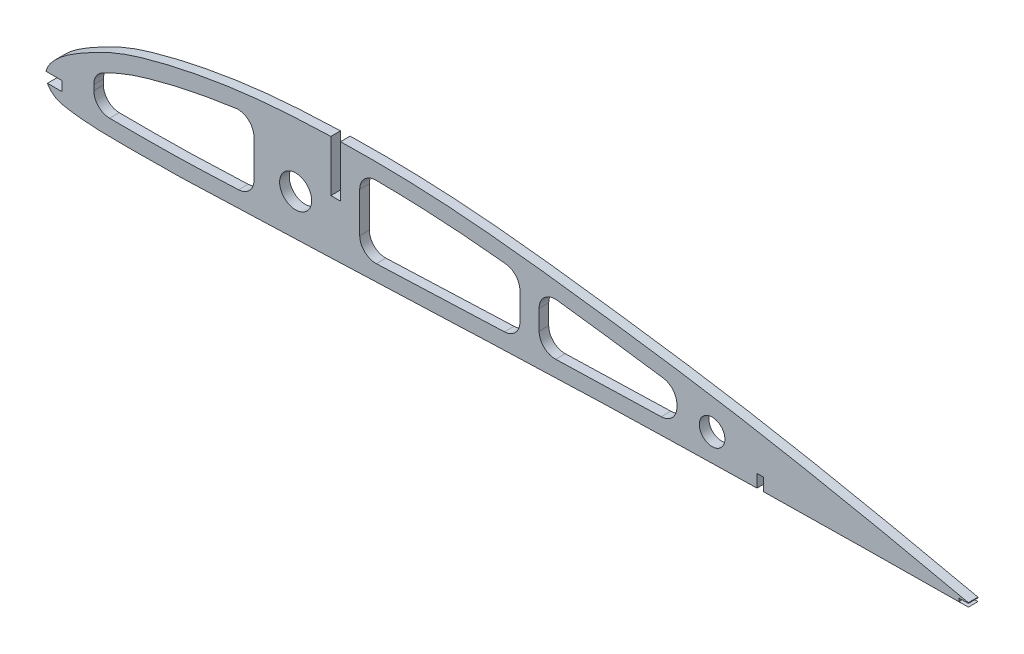
SolidWorks part; units mm, degrees
material "轻木"
ref_plane "前视基准面" through (0, 0, 0) normal (0, 0, 1) x (1, 0, 0)
ref_plane "上视基准面" through (0, 0, 0) normal (0, 1, 0) x (1, 0, 0)
ref_plane "右视基准面" through (0, 0, 0) normal (1, 0, 0) x (0, 0, -1)
other "Configuration Table"
curve "曲线1"
  spline degree 3 poles (300, 0.375, 0) (299.2857, 0.5355, 0) (297.8572, 0.8566, 0) (295.7147, 1.3378, 0) (293.5725, 1.8185, 0) (291.4302, 2.2982, 0) (289.2875, 2.7769, 0) (287.1442, 3.2543, 0) (285.001, 3.7299, 0) (282.8583, 4.2033, 0) (280.7163, 4.6744, 0) (278.5743, 5.1433, 0) (276.432, 5.6099, 0) (274.2889, 6.0741, 0) (272.145, 6.5358, 0) (269.2891, 7.1472, 0) (265.721, 7.9038, 0) (261.4399, 8.8, 0) (257.1573, 9.6847, 0) (252.8725, 10.5577, 0) (248.585, 11.4191, 0) (244.2942, 12.2686, 0) (240.0067, 13.1048, 0) (235.7231, 13.9276, 0) (231.4437, 14.735, 0) (227.1623, 15.5265, 0) (222.8779, 16.3002, 0) (218.5899, 17.0545, 0) (214.2976, 17.7876, 0) (210.0082, 18.4964, 0) (205.7223, 19.1793, 0) (201.441, 19.8388, 0) (197.1575, 20.4787, 0) (192.8717, 21.1016, 0) (188.5834, 21.71, 0) (184.2928, 22.3067, 0) (180.0042, 22.8936, 0) (175.7188, 23.4732, 0) (171.4371, 24.0431, 0) (167.1545, 24.6013, 0) (162.8704, 25.1452, 0) (158.5838, 25.6724, 0) (154.2938, 26.1804, 0) (150.0066, 26.6658, 0) (145.7226, 27.1265, 0) (141.4425, 27.5584, 0) (137.1601, 27.958, 0) (132.875, 28.3213, 0) (128.5869, 28.6439, 0) (124.2953, 28.9218, 0) (120.0053, 29.1506, 0) (115.7177, 29.3264, 0) (111.4337, 29.4514, 0) (107.1488, 29.5275, 0) (102.863, 29.5565, 0) (98.5762, 29.5401, 0) (94.2882, 29.4801, 0) (89.9957, 29.378, 0) (85.6999, 29.236, 0) (81.4026, 29.047, 0) (77.1093, 28.8043, 0) (72.8211, 28.5008, 0) (68.5389, 28.1296, 0) (64.264, 27.6835, 0) (60.7007, 27.2426, 0) (57.8461, 26.8442, 0) (55.696, 26.5216, 0) (53.5496, 26.1773, 0) (51.4067, 25.8115, 0) (49.2673, 25.4247, 0) (47.1314, 25.0171, 0) (44.9882, 24.5868, 0) (42.838, 24.1341, 0) (40.6818, 23.6568, 0) (38.5315, 23.1552, 0) (36.3875, 22.6273, 0) (34.2503, 22.0712, 0) (32.1202, 21.4847, 0) (30.3423, 20.9664, 0) (28.9132, 20.5311, 0) (27.8303, 20.1897, 0) (26.7518, 19.8362, 0) (25.6784, 19.4687, 0) (24.6112, 19.0858, 0) (23.551, 18.6856, 0) (22.4821, 18.2598, 0) (21.4059, 17.8057, 0) (20.3222, 17.3242, 0) (19.2465, 16.8243, 0) (18.1774, 16.3076, 0) (17.1139, 15.7762, 0) (16.0546, 15.2317, 0) (14.9819, 14.6674, 0) (13.8954, 14.0851, 0) (12.7977, 13.4827, 0) (11.7087, 12.8677, 0) (10.6313, 12.2387, 0) (9.5687, 11.5942, 0) (8.5237, 10.9329, 0) (7.6518, 10.3543, 0) (6.9458, 9.8665, 0) (6.3985, 9.4746, 0) (5.8573, 9.0705, 0) (5.3218, 8.651, 0) (4.7913, 8.2128, 0) (4.2653, 7.7527, 0) (3.6165, 7.1497, 0) (2.8604, 6.3846, 0) (2.0362, 5.4343, 0) (1.2959, 4.4252, 0) (0.6772, 3.3675, 0) (0.2189, 2.2697, 0) (-0.0383, 1.1392, 0) (-0.0456, 0.0749, 0) (0.1619, -0.885, 0) (0.4986, -1.7375, 0) (0.9635, -2.5517, 0) (1.5376, -3.3119, 0) (2.2026, -4.0019, 0) (2.94, -4.6051, 0) (3.6355, -5.044, 0) (4.2555, -5.3464, 0) (4.779, -5.5548, 0) (5.3118, -5.728, 0) (5.8521, -5.8723, 0) (6.398, -5.9938, 0) (6.9478, -6.0987, 0) (7.671, -6.2224, 0) (8.5669, -6.3647, 0) (9.636, -6.5177, 0) (10.7063, -6.6545, 0) (11.7778, -6.7754, 0) (12.8506, -6.8809, 0) (13.9246, -6.9713, 0) (14.9978, -7.047, 0) (16.0697, -7.1082, 0) (17.1403, -7.1566, 0) (18.2115, -7.1941, 0) (19.2831, -7.2222, 0) (20.3552, -7.2427, 0) (21.4275, -7.2573, 0) (22.4998, -7.2676, 0) (23.5718, -7.2752, 0) (24.6434, -7.2803, 0) (25.7147, -7.2832, 0) (26.7859, -7.2843, 0) (27.8572, -7.2839, 0) (28.9285, -7.2822, 0) (30.3573, -7.2788, 0) (32.1433, -7.2727, 0) (34.2864, -7.2613, 0) (36.4292, -7.2444, 0) (38.5718, -7.2208, 0) (40.7144, -7.1891, 0) (42.8572, -7.148, 0) (45.0005, -7.0962, 0) (47.1439, -7.0325, 0) (49.2871, -6.9587, 0) (51.4297, -6.8772, 0) (53.572, -6.7902, 0) (55.7143, -6.6999, 0) (57.857, -6.6086, 0) (60.7142, -6.4884, 0) (64.2858, -6.3465, 0) (68.5714, -6.1868, 0) (72.8565, -6.0353, 0) (77.1416, -5.8893, 0) (81.427, -5.7463, 0) (85.7132, -5.6038, 0) (90.0001, -5.4593, 0) (94.287, -5.3101, 0) (98.5731, -5.1566, 0) (102.8583, -4.9992, 0) (107.1431, -4.8383, 0) (111.4281, -4.6742, 0) (115.7138, -4.5074, 0) (120.0001, -4.3383, 0) (124.2865, -4.1673, 0) (128.5722, -3.9953, 0) (132.8572, -3.8233, 0) (137.142, -3.6525, 0) (141.4271, -3.4838, 0) (145.7131, -3.3181, 0) (149.9996, -3.1567, 0) (154.286, -3.0004, 0) (158.5714, -2.8495, 0) (162.8564, -2.7043, 0) (167.1412, -2.5651, 0) (171.4266, -2.4321, 0) (175.7128, -2.3056, 0) (179.9996, -2.1858, 0) (184.2862, -2.0731, 0) (188.5719, -1.9664, 0) (192.857, -1.8646, 0) (197.1419, -1.7668, 0) (201.4272, -1.6719, 0) (205.7132, -1.5788, 0) (209.9999, -1.4865, 0) (214.2864, -1.3941, 0) (218.5722, -1.3027, 0) (222.8572, -1.2136, 0) (227.142, -1.128, 0) (231.4272, -1.0471, 0) (235.7132, -0.9723, 0) (239.9998, -0.9046, 0) (244.2864, -0.8454, 0) (248.5722, -0.7928, 0) (252.8573, -0.7451, 0) (257.1422, -0.7003, 0) (261.4274, -0.6568, 0) (265.7134, -0.6127, 0) (269.2855, -0.574, 0) (272.1433, -0.5408, 0) (274.2862, -0.5157, 0) (276.4287, -0.4908, 0) (278.5712, -0.4671, 0) (280.7137, -0.4452, 0) (282.8567, -0.4258, 0) (285, -0.4096, 0) (287.1432, -0.3973, 0) (289.2862, -0.3884, 0) (291.4287, -0.3824, 0) (293.5711, -0.3786, 0) (295.7137, -0.3765, 0) (297.8567, -0.3754, 0) (299.2855, -0.3751, 0) (300, -0.375, 0) knots 0 0 0 0 0.003574 0.007146 0.010718 0.01429 0.017862 0.021434 0.025008 0.028577 0.032145 0.035713 0.03928 0.042847 0.046415 0.049985 0.057103 0.064219 0.071333 0.078448 0.085563 0.092679 0.099797 0.106885 0.11397 0.121053 0.128137 0.13522 0.142305 0.149391 0.15644 0.163488 0.170534 0.17758 0.184627 0.191675 0.198725 0.205755 0.212782 0.219809 0.226834 0.233861 0.240889 0.24792 0.254921 0.26192 0.268917 0.275914 0.28291 0.289907 0.296905 0.303879 0.310852 0.317824 0.324796 0.331771 0.338748 0.345728 0.352728 0.359727 0.366723 0.373717 0.380709 0.387701 0.394695 0.398233 0.40177 0.405307 0.408843 0.41238 0.415918 0.419457 0.42305 0.426643 0.430235 0.433828 0.43742 0.441014 0.444611 0.446459 0.448306 0.450153 0.451999 0.453844 0.455687 0.45753 0.459459 0.461388 0.463318 0.465249 0.467183 0.469121 0.471062 0.4731 0.475138 0.477173 0.479204 0.481227 0.483239 0.48524 0.486334 0.487428 0.488525 0.48963 0.490748 0.491883 0.493041 0.495071 0.497131 0.499176 0.501171 0.503098 0.50496 0.506796 0.508242 0.509728 0.511253 0.512804 0.514366 0.515919 0.517444 0.518368 0.519283 0.520192 0.521101 0.522011 0.522922 0.523833 0.525592 0.527349 0.529104 0.530859 0.532612 0.534366 0.53612 0.537863 0.539607 0.54135 0.543094 0.544839 0.546584 0.548329 0.550073 0.551817 0.55356 0.555302 0.557045 0.558788 0.560532 0.564019 0.567506 0.570992 0.574478 0.577965 0.581452 0.584939 0.588429 0.591918 0.595406 0.598895 0.602383 0.605872 0.609363 0.616342 0.623319 0.630295 0.637271 0.644247 0.651224 0.658203 0.665183 0.672161 0.679137 0.686114 0.69309 0.700068 0.707048 0.714028 0.721006 0.727983 0.73496 0.741937 0.748915 0.755896 0.762874 0.769851 0.776826 0.783801 0.790777 0.797753 0.804732 0.811709 0.818683 0.825657 0.83263 0.839604 0.846578 0.853555 0.860532 0.867506 0.874479 0.881452 0.888424 0.895399 0.902375 0.90935 0.916324 0.923296 0.930267 0.937239 0.944213 0.951188 0.954676 0.958163 0.961649 0.965135 0.96862 0.972107 0.975595 0.979082 0.982569 0.986054 0.98954 0.993026 0.996512 1 1 1 1
curve "曲线2"
  spline degree 3 poles (299.6892, 0.0825, 0) (300.1498, -0.0478, 0) (299.7114, 0.1074, 0) (299.5104, 0.1872, 0) (299.2477, 0.2871, 0) (298.8504, 0.4413, 0) (298.294, 0.6613, 0) (297.5919, 0.9463, 0) (296.8903, 1.2362, 0) (296.0644, 1.581, 0) (295.1136, 1.9799, 0) (294.0373, 2.431, 0) (292.9597, 2.8788, 0) (291.7683, 3.3665, 0) (290.4608, 3.8877, 0) (289.0365, 4.4399, 0) (287.6073, 4.9796, 0) (286.0635, 5.5484, 0) (284.4048, 6.1444, 0) (282.6311, 6.7664, 0) (280.8534, 7.377, 0) (278.9651, 8.0149, 0) (276.9667, 8.6805, 0) (274.8582, 9.373, 0) (272.7471, 10.0574, 0) (270.5382, 10.7652, 0) (268.2318, 11.4959, 0) (265.8278, 12.2485, 0) (263.4214, 12.9932, 0) (260.9293, 13.7558, 0) (258.3517, 14.5354, 0) (255.6885, 15.3308, 0) (253.0225, 16.1168, 0) (250.2835, 16.9138, 0) (247.4714, 17.7205, 0) (244.5864, 18.536, 0) (241.6982, 19.3402, 0) (238.749, 20.1489, 0) (235.7391, 20.9612, 0) (232.6684, 21.7757, 0) (229.594, 22.5763, 0) (226.4711, 23.374, 0) (223.2997, 24.1675, 0) (220.08, 24.9553, 0) (216.8561, 25.726, 0) (213.5945, 26.4871, 0) (210.2953, 27.2373, 0) (206.9588, 27.975, 0) (203.6178, 28.6919, 0) (200.2497, 29.3918, 0) (196.8549, 30.0732, 0) (193.4336, 30.7349, 0) (190.0077, 31.3718, 0) (186.5618, 31.9862, 0) (183.0963, 32.577, 0) (179.6117, 33.1436, 0) (176.1229, 33.6833, 0) (172.6234, 34.197, 0) (169.1136, 34.6844, 0) (165.5943, 35.1447, 0) (162.0713, 35.5767, 0) (158.5465, 35.9798, 0) (155.0205, 36.3535, 0) (151.4939, 36.6979, 0) (147.9646, 37.0129, 0) (144.4431, 37.2978, 0) (140.9302, 37.5529, 0) (137.4264, 37.7777, 0) (133.9208, 37.9727, 0) (130.4332, 38.1365, 0) (126.9642, 38.269, 0) (123.5147, 38.3706, 0) (120.0643, 38.4412, 0) (116.6408, 38.4803, 0) (113.2449, 38.4881, 0) (109.8772, 38.4649, 0) (106.5099, 38.4098, 0) (103.1795, 38.3231, 0) (99.8867, 38.2053, 0) (96.6323, 38.0567, 0) (93.3796, 37.8749, 0) (90.1728, 37.6618, 0) (87.0127, 37.4182, 0) (83.9, 37.1447, 0) (80.7905, 36.8368, 0) (77.7347, 36.4989, 0) (74.7332, 36.1323, 0) (71.7867, 35.7377, 0) (68.8452, 35.3075, 0) (65.9638, 34.8492, 0) (63.1431, 34.3642, 0) (60.3838, 33.8535, 0) (57.6314, 33.3063, 0) (54.9457, 32.7337, 0) (52.327, 32.1376, 0) (49.7758, 31.5197, 0) (47.2337, 30.8655, 0) (44.763, 30.1905, 0) (42.364, 29.4973, 0) (40.0371, 28.7872, 0) (37.7217, 28.0406, 0) (35.4836, 27.2778, 0) (33.323, 26.5013, 0) (31.2399, 25.7132, 0) (29.1709, 24.8888, 0) (27.1829, 24.0541, 0) (25.2756, 23.212, 0) (23.4491, 22.3647, 0) (21.6401, 21.481, 0) (19.9159, 20.5922, 0) (18.2759, 19.7016, 0) (16.7198, 18.8121, 0) (15.1846, 17.8866, 0) (13.7354, 16.9627, 0) (12.3708, 16.045, 0) (11.0909, 15.1361, 0) (9.8373, 14.192, 0) (8.6721, 13.2572, 0) (7.5935, 12.336, 0) (6.5993, 11.4319, 0) (5.6356, 10.4933, 0) (4.7571, 9.5716, 0) (3.961, 8.6731, 0) (3.2484, 7.802, 0) (2.5791, 6.9017, 0) (2.0018, 6.0303, 0) (1.5119, 5.1928, 0) (1.098, 4.3932, 0) (0.723, 3.565, 0) (0.4148, 2.7772, 0) (0.1635, 2.0409, 0) (-0.0076, 1.362, 0) (-0.0857, 0.6761, 0) (-0.0312, 0.0318, 0) (0.1575, -0.5446, 0) (0.4284, -1.0495, 0) (0.7766, -1.5095, 0) (1.2499, -1.9767, 0) (1.8739, -2.4002, 0) (2.6419, -2.7457, 0) (3.4475, -3.0028, 0) (4.3968, -3.243, 0) (5.4726, -3.4987, 0) (6.6732, -3.7581, 0) (7.8724, -3.9885, 0) (9.2039, -4.2095, 0) (10.6736, -4.4054, 0) (12.2821, -4.571, 0) (13.8972, -4.6995, 0) (15.6445, -4.8094, 0) (17.5211, -4.9053, 0) (19.5261, -4.9826, 0) (21.5305, -5.0368, 0) (23.661, -5.0721, 0) (25.9181, -5.0854, 0) (28.3014, -5.0749, 0) (30.6852, -5.0437, 0) (33.1885, -4.993, 0) (35.8107, -4.9237, 0) (38.5514, -4.8343, 0) (41.2914, -4.7299, 0) (44.1429, -4.6075, 0) (47.1057, -4.467, 0) (50.1792, -4.3077, 0) (53.2522, -4.1367, 0) (56.4269, -3.9498, 0) (59.7026, -3.7473, 0) (63.0791, -3.5293, 0) (66.4551, -3.3033, 0) (69.9209, -3.0645, 0) (73.4761, -2.8134, 0) (77.1202, -2.5502, 0) (80.764, -2.2824, 0) (84.4846, -2.0051, 0) (88.2815, -1.7191, 0) (92.1543, -1.4245, 0) (96.027, -1.128, 0) (99.9621, -0.8252, 0) (103.9592, -0.5167, 0) (108.0179, -0.2032, 0) (112.0767, 0.1098, 0) (116.1823, 0.4251, 0) (120.3344, 0.742, 0) (124.5324, 1.0596, 0) (128.7308, 1.3739, 0) (132.9595, 1.6861, 0) (137.2181, 1.9957, 0) (141.506, 2.3018, 0) (145.7945, 2.6016, 0) (150.096, 2.8954, 0) (154.41, 3.1825, 0) (158.7362, 3.4618, 0) (163.063, 3.7316, 0) (167.3848, 3.9907, 0) (171.7011, 4.2382, 0) (176.0115, 4.4733, 0) (180.3226, 4.6957, 0) (184.6083, 4.9033, 0) (188.8679, 5.0957, 0) (193.1011, 5.2721, 0) (197.335, 5.4325, 0) (201.5222, 5.5742, 0) (205.6623, 5.6969, 0) (209.7546, 5.8004, 0) (213.8473, 5.8854, 0) (217.8716, 5.9498, 0) (221.8268, 5.9942, 0) (225.7124, 6.0188, 0) (229.598, 6.0233, 0) (233.3935, 6.0071, 0) (237.0983, 5.971, 0) (240.7119, 5.9157, 0) (244.325, 5.8393, 0) (247.8275, 5.7436, 0) (251.2186, 5.6301, 0) (254.498, 5.5, 0) (257.7765, 5.3484, 0) (260.9253, 5.1809, 0) (263.9441, 4.9996, 0) (266.8324, 4.8058, 0) (269.7191, 4.5899, 0) (272.4587, 4.362, 0) (275.0509, 4.1249, 0) (277.4951, 3.8799, 0) (279.9368, 3.6105, 0) (282.2113, 3.3338, 0) (284.3185, 3.0537, 0) (286.2585, 2.7745, 0) (288.195, 2.4723, 0) (289.9467, 2.1761, 0) (291.5141, 1.8919, 0) (292.8979, 1.6262, 0) (294.2788, 1.3456, 0) (295.4709, 1.0894, 0) (296.4751, 0.8638, 0) (297.2928, 0.6738, 0) (298.1076, 0.4784, 0) (298.7442, 0.3204, 0) (299.1896, 0.208, 0) (299.4728, 0.1348, 0) (299.6892, 0.0825, 0) (300.1498, -0.0478, 0) (299.7114, 0.1074, 0) knots -0.001345 -0.000897 -0.000449 0 0.000432 0.000863 0.001295 0.001726 0.002951 0.004176 0.0054 0.006625 0.008509 0.010392 0.012274 0.014158 0.016623 0.019088 0.021553 0.024019 0.027053 0.030085 0.033118 0.036152 0.039734 0.043315 0.046896 0.050478 0.054544 0.058608 0.062672 0.066738 0.071224 0.075709 0.080193 0.084679 0.089518 0.094356 0.099193 0.104032 0.10916 0.114286 0.119411 0.124539 0.129889 0.135237 0.140585 0.145936 0.151451 0.156964 0.162478 0.167993 0.173617 0.17924 0.184862 0.190486 0.196184 0.20188 0.207576 0.213274 0.219003 0.22473 0.230457 0.236185 0.241905 0.247622 0.253339 0.259058 0.264725 0.270389 0.276054 0.281721 0.287291 0.29286 0.298428 0.303998 0.309434 0.314867 0.320301 0.325737 0.330995 0.336251 0.341507 0.346766 0.351809 0.356851 0.361892 0.366936 0.371734 0.37653 0.381327 0.386125 0.390654 0.395182 0.399709 0.404238 0.408475 0.41271 0.416945 0.421182 0.425109 0.429034 0.432959 0.436885 0.44048 0.444073 0.447666 0.451261 0.454511 0.457759 0.461007 0.464256 0.467149 0.470041 0.472933 0.475826 0.47836 0.480893 0.483425 0.485956 0.488123 0.490291 0.49246 0.494634 0.496453 0.49827 0.500081 0.501882 0.503328 0.504776 0.506239 0.507727 0.50887 0.510003 0.51111 0.512198 0.513104 0.514027 0.514959 0.515886 0.517235 0.518584 0.51995 0.521324 0.523324 0.525303 0.52727 0.529235 0.531836 0.534446 0.537062 0.539679 0.542921 0.546158 0.549393 0.552628 0.556473 0.560319 0.564166 0.568014 0.57244 0.576864 0.581288 0.585714 0.590681 0.595647 0.600613 0.605581 0.611042 0.616501 0.62196 0.627422 0.633319 0.639214 0.645109 0.651006 0.657275 0.663542 0.669809 0.676078 0.682648 0.689216 0.695784 0.702355 0.70915 0.715943 0.722736 0.729531 0.73647 0.743406 0.750342 0.757281 0.764278 0.771273 0.778268 0.785265 0.792232 0.799197 0.806162 0.81313 0.819969 0.826805 0.833641 0.840479 0.847087 0.853692 0.860297 0.866904 0.873175 0.879445 0.885714 0.891986 0.897819 0.90365 0.909481 0.915314 0.920611 0.925907 0.931202 0.936499 0.941172 0.945842 0.950513 0.955185 0.95915 0.963114 0.967077 0.971042 0.974206 0.977368 0.98053 0.983693 0.985968 0.988241 0.990515 0.992789 0.994144 0.995498 0.996852 0.998206 0.998655 0.999103 0.999551 1 1.000432 1.000863 1.001295 periodic
sketch "草图1" plane through (0, 0, 0) normal (0, 0, 1) x (1, 0, 0)
  line L1 (290, 2.6177) -> (290, -0.3866)
  line L2 (289, 1.8162) -> (289, 0.6101)
  line L3 (0, 0) -> (0, 30) construction
  line L4 (-6, -1.5) -> (6, -1.5)
  line L5 (-6, -1.5) -> (-6, 1.5)
  line L6 (-6, 1.5) -> (6, 1.5)
  line L7 (6, -1.5) -> (6, 1.5)
  line L8 (-6, -1.5) -> (6, 1.5) construction
  line L9 (-6, 1.5) -> (6, -1.5) construction
  line L10 (-1000, 0) -> (49000, 0) construction
  line L11 (90, 29.3715) -> (93, 29.3715)
  line L12 (90, 29.3715) -> (90, 12.3715)
  line L13 (90, 12.3715) -> (93, 12.3715)
  line L14 (93, 29.3715) -> (93, 12.3715)
  line L16 (223, -1.2113) -> (225, -1.2113)
  line L17 (223, -1.2113) -> (223, 3.7887)
  line L18 (223, 3.7887) -> (225, 3.7887)
  line L19 (225, -1.2113) -> (225, 3.7887)
  line L20 (289, 0.6101) -> (286, 0.6101)
  line L21 (289, 0.6101) -> (289, 1.6101)
  line L22 (289, 1.6101) -> (286, 1.6101)
  line L23 (286, 0.6101) -> (286, 1.6101)
  circle A0 centre (79, 8) radius 5
  circle A1 centre (209, 8) radius 4
  spline S0 degree 3 poles (2664.3845, 5390.8144) (1028.5028, -174.9169) (663.7122, -81.3233) (295.7147, 1.3378) (293.5725, 1.8185) (291.4302, 2.2982) (289.2875, 2.7769) (287.1442, 3.2543) (285.001, 3.7299) (282.8583, 4.2033) (280.7163, 4.6744) (278.5743, 5.1433) (276.432, 5.6099) (274.2889, 6.0741) (272.145, 6.5358) (269.2891, 7.1472) (265.721, 7.9038) (261.4399, 8.8) (257.1573, 9.6847) (252.8725, 10.5577) (248.585, 11.4191) (244.2942, 12.2686) (240.0067, 13.1048) (234.2978, 14.2013) (228.5907, 15.2685) (222.8779, 16.3002) (218.5899, 17.0545) (214.2976, 17.7876) (210.0082, 18.4964) (205.7223, 19.1793) (201.441, 19.8388) (197.1575, 20.4787) (192.8717, 21.1016) (188.5834, 21.71) (184.2928, 22.3067) (180.0042, 22.8936) (175.7188, 23.4732) (171.4371, 24.0431) (167.1545, 24.6013) (162.8704, 25.1452) (158.5838, 25.6724) (154.2938, 26.1804) (150.0066, 26.6658) (145.7226, 27.1265) (141.4425, 27.5584) (137.1601, 27.958) (132.875, 28.3213) (128.5869, 28.6439) (124.2953, 28.9218) (120.0053, 29.1506) (115.7177, 29.3264) (111.4337, 29.4514) (107.1488, 29.5275) (102.863, 29.5565) (98.5762, 29.5401) (94.2882, 29.4801) (89.9957, 29.378) (85.6999, 29.236) (81.4026, 29.047) (77.1093, 28.8043) (72.8211, 28.5008) (68.5389, 28.1296) (64.264, 27.6835) (60.7007, 27.2426) (57.1284, 26.744) (53.5478, 26.188) (49.9791, 25.5605) (47.1314, 25.0171) (44.9882, 24.5868) (42.838, 24.1341) (40.6818, 23.6568) (38.5315, 23.1552) (36.3875, 22.6273) (34.2503, 22.0712) (32.1202, 21.4847) (30.3423, 20.9664) (28.9132, 20.5311) (27.8303, 20.1897) (26.7518, 19.8362) (25.6784, 19.4687) (24.6112, 19.0858) (23.551, 18.6856) (22.4821, 18.2598) (21.4059, 17.8057) (20.3222, 17.3242) (19.2465, 16.8243) (18.1774, 16.3076) (17.1139, 15.7762) (16.0546, 15.2317) (14.9819, 14.6674) (13.8954, 14.0851) (12.7977, 13.4827) (11.7087, 12.8677) (10.6313, 12.2387) (9.5687, 11.5942) (8.5237, 10.9329) (7.6518, 10.3543) (6.9458, 9.8665) (6.3985, 9.4746) (5.8573, 9.0705) (5.3218, 8.651) (4.7913, 8.2128) (4.2653, 7.7527) (3.6165, 7.1497) (2.8604, 6.3846) (2.0362, 5.4343) (1.2959, 4.4252) (0.6772, 3.3675) (0.2189, 2.2697) (-0.0383, 1.1392) (-0.0456, 0.0749) (0.1619, -0.885) (0.4986, -1.7375) (0.9635, -2.5517) (1.5376, -3.3119) (2.2026, -4.0019) (2.94, -4.6051) (3.6355, -5.044) (4.2555, -5.3464) (4.779, -5.5548) (5.3118, -5.728) (5.8521, -5.8723) (6.398, -5.9938) (6.9478, -6.0987) (7.671, -6.2224) (8.5669, -6.3647) (9.9918, -6.5686) (11.4199, -6.7402) (12.8506, -6.8809) (13.9246, -6.9713) (14.9978, -7.047) (16.0697, -7.1082) (17.1403, -7.1566) (18.2115, -7.1941) (19.2831, -7.2222) (20.3552, -7.2427) (21.4275, -7.2573) (22.4998, -7.2676) (23.5718, -7.2752) (24.6434, -7.2803) (25.7147, -7.2832) (27.143, -7.2847) (28.5715, -7.283) (30.3573, -7.2788) (32.1433, -7.2727) (34.2864, -7.2613) (36.4292, -7.2444) (38.5718, -7.2208) (40.7144, -7.1891) (42.8572, -7.148) (45.0005, -7.0962) (47.1439, -7.0325) (49.2871, -6.9587) (51.4297, -6.8772) (54.2862, -6.7612) (57.1429, -6.6386) (60.7142, -6.4884) (64.2858, -6.3465) (69.9995, -6.1336) (75.7132, -5.9369) (81.427, -5.7463) (85.7132, -5.6038) (90.0001, -5.4593) (94.287, -5.3101) (98.5731, -5.1566) (102.8583, -4.9992) (108.5717, -4.7846) (114.2856, -4.5638) (120.0001, -4.3383) (124.2865, -4.1673) (128.5722, -3.9953) (132.8572, -3.8233) (137.142, -3.6525) (141.4271, -3.4838) (145.7131, -3.3181) (149.9996, -3.1567) (154.286, -3.0004) (158.5714, -2.8495) (164.2846, -2.656) (171.4272, -2.4288) (179.9991, -2.1823) (187.1429, -2.0003) (192.857, -1.8646) (197.1419, -1.7668) (201.4272, -1.6719) (205.7132, -1.5788) (209.9999, -1.4865) (214.2864, -1.3941) (218.5722, -1.3027) (222.8572, -1.2136) (227.142, -1.128) (231.4272, -1.0471) (235.7132, -0.9723) (239.9998, -0.9046) (244.2864, -0.8454) (248.5722, -0.7928) (252.8573, -0.7451) (258.5708, -0.6854) (264.285, -0.6282) (269.2855, -0.574) (272.1433, -0.5408) (274.2862, -0.5157) (276.4287, -0.4908) (278.5712, -0.4671) (280.7137, -0.4452) (282.8567, -0.4258) (285, -0.4096) (287.1432, -0.3973) (289.2862, -0.3884) (291.4287, -0.3824) (293.5711, -0.3786) (295.7137, -0.3765) (581.7502, -0.2419) (867.0763, -15.0378) (1150.1739, 5872.6366) knots -1.830244 -1.830244 -1.830244 -1.830244 0.003574 0.007146 0.010718 0.01429 0.017862 0.021434 0.025008 0.028577 0.032145 0.035713 0.03928 0.042847 0.046415 0.049985 0.057103 0.064219 0.071333 0.078448 0.085563 0.092679 0.099797 0.106885 0.121053 0.128137 0.13522 0.142305 0.149391 0.15644 0.163488 0.170534 0.17758 0.184627 0.191675 0.198725 0.205755 0.212782 0.219809 0.226834 0.233861 0.240889 0.24792 0.254921 0.26192 0.268917 0.275914 0.28291 0.289907 0.296905 0.303879 0.310852 0.317824 0.324796 0.331771 0.338748 0.345728 0.352728 0.359727 0.366723 0.373717 0.380709 0.387701 0.394695 0.398233 0.405307 0.41238 0.415918 0.419457 0.42305 0.426643 0.430235 0.433828 0.43742 0.441014 0.444611 0.446459 0.448306 0.450153 0.451999 0.453844 0.455687 0.45753 0.459459 0.461388 0.463318 0.465249 0.467183 0.469121 0.471062 0.4731 0.475138 0.477173 0.479204 0.481227 0.483239 0.48524 0.486334 0.487428 0.488525 0.48963 0.490748 0.491883 0.493041 0.495071 0.497131 0.499176 0.501171 0.503098 0.50496 0.506796 0.508242 0.509728 0.511253 0.512804 0.514366 0.515919 0.517444 0.518368 0.519283 0.520192 0.521101 0.522011 0.522922 0.523833 0.525592 0.527349 0.530859 0.532612 0.534366 0.53612 0.537863 0.539607 0.54135 0.543094 0.544839 0.546584 0.548329 0.550073 0.551817 0.55356 0.555302 0.558788 0.560532 0.564019 0.567506 0.570992 0.574478 0.577965 0.581452 0.584939 0.588429 0.591918 0.595406 0.598895 0.605872 0.609363 0.616342 0.623319 0.637271 0.644247 0.651224 0.658203 0.665183 0.672161 0.679137 0.686114 0.700068 0.707048 0.714028 0.721006 0.727983 0.73496 0.741937 0.748915 0.755896 0.762874 0.769851 0.776826 0.790777 0.804732 0.818683 0.825657 0.83263 0.839604 0.846578 0.853555 0.860532 0.867506 0.874479 0.881452 0.888424 0.895399 0.902375 0.90935 0.916324 0.923296 0.930267 0.944213 0.951188 0.954676 0.958163 0.961649 0.965135 0.96862 0.972107 0.975595 0.979082 0.982569 0.986054 0.98954 0.993026 0.996512 2.385691 2.385691 2.385691 2.385691 only from (300, 0.375) to (300, -0.375) construction
  spline S1 degree 3 poles (290, 2.6177) (289.0482, 2.8302) (287.3817, 3.2016) (285.001, 3.7299) (282.8583, 4.2033) (280.7163, 4.6744) (278.5743, 5.1433) (276.432, 5.6099) (274.2889, 6.0741) (272.145, 6.5358) (269.2891, 7.1472) (265.721, 7.9038) (261.4399, 8.8) (257.1573, 9.6847) (252.8725, 10.5577) (248.585, 11.4191) (244.2942, 12.2686) (240.0067, 13.1048) (234.2978, 14.2013) (228.5907, 15.2685) (222.8779, 16.3002) (218.5899, 17.0545) (214.2976, 17.7876) (210.0082, 18.4964) (205.7223, 19.1793) (201.441, 19.8388) (197.1575, 20.4787) (192.8717, 21.1016) (188.5834, 21.71) (184.2928, 22.3067) (180.0042, 22.8936) (175.7188, 23.4732) (171.4371, 24.0431) (167.1545, 24.6013) (162.8704, 25.1452) (158.5838, 25.6724) (154.2938, 26.1804) (150.0066, 26.6658) (145.7226, 27.1265) (141.4425, 27.5584) (137.1601, 27.958) (132.875, 28.3213) (128.5869, 28.6439) (124.2953, 28.9218) (120.0053, 29.1506) (115.7177, 29.3264) (111.4337, 29.4514) (107.1488, 29.5275) (102.863, 29.5565) (98.5762, 29.5401) (94.2882, 29.4801) (89.9957, 29.378) (85.6999, 29.236) (81.4026, 29.047) (77.1093, 28.8043) (72.8211, 28.5008) (68.5389, 28.1296) (64.264, 27.6835) (60.7007, 27.2426) (57.1284, 26.744) (53.5478, 26.188) (49.9791, 25.5605) (47.1314, 25.0171) (44.9882, 24.5868) (42.838, 24.1341) (40.6818, 23.6568) (38.5315, 23.1552) (36.3875, 22.6273) (34.2503, 22.0712) (32.1202, 21.4847) (30.3423, 20.9664) (28.9132, 20.5311) (27.8303, 20.1897) (26.7518, 19.8362) (25.6784, 19.4687) (24.6112, 19.0858) (23.551, 18.6856) (22.4821, 18.2598) (21.4059, 17.8057) (20.3222, 17.3242) (19.2465, 16.8243) (18.1774, 16.3076) (17.1139, 15.7762) (16.0546, 15.2317) (14.9819, 14.6674) (13.8954, 14.0851) (12.7977, 13.4827) (11.7087, 12.8677) (10.6313, 12.2387) (9.5687, 11.5942) (8.5237, 10.9329) (7.6518, 10.3543) (6.9458, 9.8665) (6.3985, 9.4746) (5.8573, 9.0705) (5.3218, 8.651) (4.7913, 8.2128) (4.2653, 7.7527) (3.6165, 7.1497) (2.8604, 6.3846) (2.0362, 5.4343) (1.2959, 4.4252) (0.6772, 3.3675) (0.2189, 2.2697) (-0.0383, 1.1392) (-0.0456, 0.0749) (0.1619, -0.885) (0.4986, -1.7375) (0.9635, -2.5517) (1.5376, -3.3119) (2.2026, -4.0019) (2.94, -4.6051) (3.6355, -5.044) (4.2555, -5.3464) (4.779, -5.5548) (5.3118, -5.728) (5.8521, -5.8723) (6.398, -5.9938) (6.9478, -6.0987) (7.671, -6.2224) (8.5669, -6.3647) (9.9918, -6.5686) (11.4199, -6.7402) (12.8506, -6.8809) (13.9246, -6.9713) (14.9978, -7.047) (16.0697, -7.1082) (17.1403, -7.1566) (18.2115, -7.1941) (19.2831, -7.2222) (20.3552, -7.2427) (21.4275, -7.2573) (22.4998, -7.2676) (23.5718, -7.2752) (24.6434, -7.2803) (25.7147, -7.2832) (27.143, -7.2847) (28.5715, -7.283) (30.3573, -7.2788) (32.1433, -7.2727) (34.2864, -7.2613) (36.4292, -7.2444) (38.5718, -7.2208) (40.7144, -7.1891) (42.8572, -7.148) (45.0005, -7.0962) (47.1439, -7.0325) (49.2871, -6.9587) (51.4297, -6.8772) (54.2862, -6.7612) (57.1429, -6.6386) (60.7142, -6.4884) (64.2858, -6.3465) (69.9995, -6.1336) (75.7132, -5.9369) (81.427, -5.7463) (85.7132, -5.6038) (90.0001, -5.4593) (94.287, -5.3101) (98.5731, -5.1566) (102.8583, -4.9992) (108.5717, -4.7846) (114.2856, -4.5638) (120.0001, -4.3383) (124.2865, -4.1673) (128.5722, -3.9953) (132.8572, -3.8233) (137.142, -3.6525) (141.4271, -3.4838) (145.7131, -3.3181) (149.9996, -3.1567) (154.286, -3.0004) (158.5714, -2.8495) (164.2846, -2.656) (171.4272, -2.4288) (179.9991, -2.1823) (187.1429, -2.0003) (192.857, -1.8646) (197.1419, -1.7668) (201.4272, -1.6719) (205.7132, -1.5788) (209.9999, -1.4865) (214.2864, -1.3941) (218.5722, -1.3027) (222.8572, -1.2136) (227.142, -1.128) (231.4272, -1.0471) (235.7132, -0.9723) (239.9998, -0.9046) (244.2864, -0.8454) (248.5722, -0.7928) (252.8573, -0.7451) (258.5708, -0.6854) (264.285, -0.6282) (269.2855, -0.574) (272.1433, -0.5408) (274.2862, -0.5157) (276.4287, -0.4908) (278.5712, -0.4671) (280.7137, -0.4452) (282.8567, -0.4258) (285, -0.4096) (287.1432, -0.3973) (288.8099, -0.3904) (289.7621, -0.3873) (290, -0.3866) knots 0.016674 0.016674 0.016674 0.016674 0.021434 0.025008 0.028577 0.032145 0.035713 0.03928 0.042847 0.046415 0.049985 0.057103 0.064219 0.071333 0.078448 0.085563 0.092679 0.099797 0.106885 0.121053 0.128137 0.13522 0.142305 0.149391 0.15644 0.163488 0.170534 0.17758 0.184627 0.191675 0.198725 0.205755 0.212782 0.219809 0.226834 0.233861 0.240889 0.24792 0.254921 0.26192 0.268917 0.275914 0.28291 0.289907 0.296905 0.303879 0.310852 0.317824 0.324796 0.331771 0.338748 0.345728 0.352728 0.359727 0.366723 0.373717 0.380709 0.387701 0.394695 0.398233 0.405307 0.41238 0.415918 0.419457 0.42305 0.426643 0.430235 0.433828 0.43742 0.441014 0.444611 0.446459 0.448306 0.450153 0.451999 0.453844 0.455687 0.45753 0.459459 0.461388 0.463318 0.465249 0.467183 0.469121 0.471062 0.4731 0.475138 0.477173 0.479204 0.481227 0.483239 0.48524 0.486334 0.487428 0.488525 0.48963 0.490748 0.491883 0.493041 0.495071 0.497131 0.499176 0.501171 0.503098 0.50496 0.506796 0.508242 0.509728 0.511253 0.512804 0.514366 0.515919 0.517444 0.518368 0.519283 0.520192 0.521101 0.522011 0.522922 0.523833 0.525592 0.527349 0.530859 0.532612 0.534366 0.53612 0.537863 0.539607 0.54135 0.543094 0.544839 0.546584 0.548329 0.550073 0.551817 0.55356 0.555302 0.558788 0.560532 0.564019 0.567506 0.570992 0.574478 0.577965 0.581452 0.584939 0.588429 0.591918 0.595406 0.598895 0.605872 0.609363 0.616342 0.623319 0.637271 0.644247 0.651224 0.658203 0.665183 0.672161 0.679137 0.686114 0.700068 0.707048 0.714028 0.721006 0.727983 0.73496 0.741937 0.748915 0.755896 0.762874 0.769851 0.776826 0.790777 0.804732 0.818683 0.825657 0.83263 0.839604 0.846578 0.853555 0.860532 0.867506 0.874479 0.881452 0.888424 0.895399 0.902375 0.90935 0.916324 0.923296 0.930267 0.944213 0.951188 0.954676 0.958163 0.961649 0.965135 0.96862 0.972107 0.975595 0.979082 0.982569 0.98373 0.98373 0.98373 0.98373
  spline S2 degree 1 poles (289, 1.8162) (289, 0.6101) knots 0 0 1 1 construction
  spline S3 degree 3 poles (289, 1.8162) (276.9573, 4.5023) (258.8616, 8.3976) (234.6482, 13.1528) (216.4485, 16.4789) (198.1829, 19.3716) (179.8506, 21.9241) (161.5032, 24.3586) (143.1279, 26.4732) (124.7122, 28.0438) (106.2546, 28.676) (87.7718, 28.43) (72.4033, 27.5865) (60.1859, 26.2263) (51.081, 24.7981) (42.0339, 23.0001) (34.582, 21.1749) (28.6974, 19.4456) (24.362, 17.9834) (20.1748, 16.2079) (16.0789, 14.1399) (12.0403, 11.9468) (8.1401, 9.5604) (5.1537, 7.3164) (3.1001, 5.2006) (1.8138, 3.4707) (0.9689, 1.5796) (0.9059, -0.2656) (1.7459, -2.0716) (3.1431, -3.6011) (4.8543, -4.6194) (6.9276, -5.1056) (9.209, -5.4548) (12.22, -5.8429) (16.0201, -6.1427) (20.6095, -6.2611) (25.2315, -6.2869) (31.3974, -6.2803) (39.1073, -6.2407) (48.3368, -6.0221) (57.5799, -5.613) (66.8407, -5.2429) (76.0966, -4.9217) (88.436, -4.516) (103.8531, -3.9731) (122.3546, -3.2481) (140.8578, -2.4955) (159.3685, -1.8041) (177.8842, -1.2225) (196.4034, -0.7749) (214.9166, -0.3802) (233.434, 0.0126) (251.9612, 0.2567) (270.4719, 0.4292) (282.8248, 0.5874) (289, 0.6101) knots 0.017978 0.017978 0.017978 0.017978 0.078237 0.108366 0.138495 0.168624 0.198753 0.228882 0.259011 0.28914 0.319269 0.349398 0.379527 0.394592 0.409656 0.424721 0.439785 0.447318 0.45485 0.462382 0.469915 0.477447 0.484979 0.492511 0.496277 0.500044 0.50381 0.507576 0.511342 0.515108 0.518874 0.52264 0.526407 0.530173 0.537705 0.545237 0.552769 0.560302 0.575366 0.590431 0.605495 0.62056 0.635624 0.650689 0.680818 0.710947 0.741076 0.771205 0.801334 0.831463 0.861593 0.891722 0.921851 0.95198 0.982109 0.982109 0.982109 0.982109
  point P8 (0, 0)
  dimension "D9" = 10
  dimension "D10" = 8
  dimension "D1" = 290
  dimension "D2" = 1
  dimension "D3" = 12
  dimension "D4" = 3
  dimension "D5" = 30
  dimension "D6" = 3
  dimension "D7" = 17
  dimension "D8" = 90
  dimension "D11" = 130
  dimension "D12" = 11
  dimension "D13" = 8
  dimension "D14" = 5
  dimension "D15" = 2
  dimension "D16" = 130
  dimension "D17" = 1
  dimension "D18" = 3
extrude "凸台-拉伸1" add sketch "草图1" along normal blind 3 contours L2 S3 | S1 L1
sketch "草图3" plane through (0, 0, 0) normal (0, 0, 1) x (1, 0, 0)
  line L12 (16, 5.403) -> (16, 3.7496)
  line L13 (66, 16.1752) -> (66, 4.5297)
  line L14 (99, 18.546) -> (99, 6.0517)
  line L15 (149, 16.2416) -> (149, 7.6232)
  line L16 (155, 14.4146) -> (155, 8.2048)
  line L17 (198, 9.9673) -> (198, 9.1407)
  line L18 (93, 28.4491) -> (93, 12.3715) construction
  arc A19 (198, 9.1407) -> (193.1165, 4.142) centre (193, 9.1407) cw
  arc A20 (198, 9.9673) -> (193.7184, 14.9154) centre (193, 9.9673) ccw
  arc A21 (155, 8.2048) -> (160.1704, 3.2078) centre (160, 8.2048) ccw
  arc A22 (155, 14.4146) -> (160.6135, 19.3768) centre (160, 14.4146) cw
  arc A23 (149, 7.6232) -> (144.1914, 2.6268) centre (144, 7.6232) cw
  arc A24 (149, 16.2416) -> (144.5132, 21.2152) centre (144, 16.2416) ccw
  arc A25 (99, 6.0517) -> (104.1864, 1.0552) centre (104, 6.0517) ccw
  arc A26 (99, 18.546) -> (104.0243, 23.5459) centre (104, 18.546) cw
  arc A27 (66, 16.1752) -> (60.3235, 21.1292) centre (61, 16.1752) ccw
  arc A28 (66, 4.5297) -> (61.2015, -0.4662) centre (61, 4.5297) cw
  arc A29 (16, 3.7496) -> (20.9267, -1.2499) centre (21, 3.7496) ccw
  arc A30 (16, 5.403) -> (18.6935, 9.8392) centre (21, 5.403) cw
  spline S4 degree 3 poles (3011.0342, -9526.4501) (72.6327, -36.799) (2.7186, 5.4191) (6.0465, 0.6803) (6.0902, 0.6246) (6.1868, 0.5153) (6.2397, 0.4617) (6.3456, 0.3655) (6.3976, 0.3236) (6.5437, 0.2182) (6.6312, 0.1692) (6.7722, 0.1112) (6.804, 0.099) (6.8878, 0.0698) (6.9381, 0.0536) (7.1139, 0.0015) (7.2645, -0.0375) (7.537, -0.0984) (7.6355, -0.1192) (7.8472, -0.1616) (7.9613, -0.1834) (8.3094, -0.2477) (8.5533, -0.2893) (9.0582, -0.3705) (9.3192, -0.41) (9.8531, -0.4875) (10.1264, -0.5257) (10.9344, -0.635) (11.4671, -0.7017) (12.5267, -0.821) (13.0591, -0.8742) (14.6647, -1.0159) (15.7434, -1.0862) (17.929, -1.1862) (19.0402, -1.2168) (21.2997, -1.2581) (22.4443, -1.2693) (24.7448, -1.282) (25.9034, -1.2838) (29.3811, -1.2835) (31.7096, -1.2772) (36.344, -1.2483) (38.6522, -1.2235) (43.2612, -1.1389) (45.5633, -1.0801) (50.1682, -0.9268) (52.4816, -0.8311) (57.1372, -0.634) (59.4794, -0.5349) (64.1588, -0.348) (66.5002, -0.2589) (73.5178, -0.0049) (78.1885, 0.1484) (87.5159, 0.4597) (92.1745, 0.6196) (101.4932, 0.9531) (106.1515, 1.1269) (120.1319, 1.6658) (129.4563, 2.0501) (148.1311, 2.7844) (157.4781, 3.1298) (171.5046, 3.5762) (176.182, 3.7134) (185.5345, 3.9625) (190.2088, 4.0755) (199.5523, 4.2901) (204.2219, 4.392) (666.7328, 14.3082) (1105.7326, 26.3753) (9056.442, -4621.7128) knots -0.352895 -0.352895 -0.352895 -0.352895 0.003906 0.003906 0.007813 0.007813 0.011719 0.011719 0.015625 0.015625 0.023438 0.023438 0.025391 0.025391 0.027344 0.027344 0.03125 0.03125 0.033203 0.033203 0.035156 0.035156 0.039063 0.039063 0.042969 0.042969 0.046875 0.046875 0.054688 0.054688 0.0625 0.0625 0.078125 0.078125 0.09375 0.09375 0.109375 0.109375 0.125 0.125 0.15625 0.15625 0.1875 0.1875 0.21875 0.21875 0.25 0.25 0.28125 0.28125 0.3125 0.3125 0.375 0.375 0.4375 0.4375 0.5 0.5 0.625 0.625 0.75 0.75 0.8125 0.8125 0.875 0.875 0.9375 0.9375 7.066999 7.066999 7.066999 7.066999 only from (5.9323, 0.8564) to (222.8977, 4.7881)
  spline S8 degree 3 poles (2926.8241, 6122.8469) (1443.6696, -590.6275) (877.6825, -127.0186) (255.6753, 3.881) (247.6023, 5.5193) (235.4757, 7.8705) (231.4302, 8.6379) (223.342, 10.1274) (219.2984, 10.8484) (211.208, 12.2244) (207.156, 12.8806) (199.0386, 14.1387) (194.9733, 14.7397) (186.8242, 15.9029) (182.7409, 16.4659) (174.5659, 17.5758) (170.4813, 18.121) (158.2342, 19.697) (150.0783, 20.6696) (137.8564, 21.8798) (133.7874, 22.2409) (125.6593, 22.8404) (121.6016, 23.0755) (-425.9959, 45.3738) (-1046.7765, -1151.5762) (1643.7683, 6682.8668) knots -9.390867 -9.390867 -9.390867 -9.390867 0.125 0.125 0.25 0.25 0.3125 0.3125 0.375 0.375 0.4375 0.4375 0.5 0.5 0.5625 0.5625 0.625 0.625 0.75 0.75 0.8125 0.8125 0.875 0.875 9.23317 9.23317 9.23317 9.23317 only from (287.9115, -3.0638) to (93.1104, 23.4504)
  spline S9 degree 3 poles (193.7184, 14.9154) (192.779, 15.0518) (191.8391, 15.1871) (186.8242, 15.9029) (182.7409, 16.4659) (174.5659, 17.5758) (170.4813, 18.121) (164.47, 18.8945) (162.5415, 19.1384) (160.6135, 19.3768) knots 0.485575 0.485575 0.485575 0.485575 0.5 0.5 0.5625 0.5625 0.625 0.625 0.654532 0.654532 0.654532 0.654532
  spline S11 degree 3 poles (-89.5982, 3979.7688) (540.3605, -251.1856) (289.0914, 44.3212) (64.1587, 21.6485) (60.4651, 21.183) (53.1092, 20.0468) (49.4459, 19.3843) (42.1587, 17.8687) (38.5334, 17.0196) (33.149, 15.5462) (31.3629, 15.0224) (27.821, 13.8802) (26.0672, 13.2533) (22.6358, 11.8127) (20.9579, 11.0048) (17.648, 9.3036) (16.0082, 8.4228) (13.5937, 7.0224) (12.7968, 6.5418) (11.2302, 5.5376) (10.459, 5.016) (8.9706, 3.8992) (8.2535, 3.3022) (7.272, 2.3101) (6.9596, 1.9643) (6.5302, 1.4143) (6.3938, 1.2256) (6.2082, 0.9302) (6.1495, 0.8297) (6.069, 0.675) (6.0433, 0.6225) (6.0083, 0.5426) (5.9972, 0.5158) (5.9815, 0.4751) (5.9764, 0.4615) (5.9691, 0.441) (5.9667, 0.4341) (5.9633, 0.4238) (5.9621, 0.4203) (5.9605, 0.4151) (5.9599, 0.4133) (5.9205, 0.287) (-3.2683, -15.5798) (1962.8471, 3341.8674) knots -0.644724 -0.644724 -0.644724 -0.644724 0.022329 0.022329 0.033494 0.033494 0.044659 0.044659 0.055823 0.055823 0.061406 0.061406 0.066988 0.066988 0.07257 0.07257 0.078153 0.078153 0.080944 0.080944 0.083735 0.083735 0.086526 0.086526 0.087922 0.087922 0.08862 0.08862 0.088968 0.088968 0.089143 0.089143 0.08923 0.08923 0.089274 0.089274 0.089296 0.089296 0.089306 0.089306 0.089312 0.089312 0.089704 0.089704 0.089704 0.089704 only from (90.1451, 23.3745) to (5.9578, 0.4064)
  spline S12 degree 3 poles (60.3235, 21.1292) (59.1433, 20.9681) (57.9644, 20.7967) (53.1092, 20.0468) (49.4459, 19.3843) (42.1587, 17.8687) (38.5334, 17.0196) (33.149, 15.5462) (31.3629, 15.0224) (27.821, 13.8802) (26.0672, 13.2533) (22.6358, 11.8127) (20.9579, 11.0048) (19.0996, 10.0497) (18.8964, 9.9447) (18.6935, 9.8392) knots 0.02992 0.02992 0.02992 0.02992 0.033494 0.033494 0.044659 0.044659 0.055823 0.055823 0.061406 0.061406 0.066988 0.066988 0.07257 0.07257 0.073256 0.073256 0.073256 0.073256
  spline S13 degree 3 poles (20.9267, -1.2499) (21.8097, -1.2628) (22.7004, -1.2707) (24.7448, -1.282) (25.9034, -1.2838) (29.3811, -1.2835) (31.7096, -1.2772) (36.344, -1.2483) (38.6522, -1.2235) (43.2612, -1.1389) (45.5633, -1.0801) (50.1682, -0.9268) (52.4816, -0.8311) (56.9324, -0.6427) (59.0674, -0.5523) (61.2015, -0.4662) knots 0.097229 0.097229 0.097229 0.097229 0.109375 0.109375 0.125 0.125 0.15625 0.15625 0.1875 0.1875 0.21875 0.21875 0.25 0.25 0.278501 0.278501 0.278501 0.278501
  spline S14 degree 3 poles (104.1864, 1.0552) (106.3946, 1.1375) (108.6029, 1.2214) (120.1319, 1.6658) (129.4563, 2.0501) (140.5926, 2.488) (142.3918, 2.5579) (144.1914, 2.6268) knots 0.470377 0.470377 0.470377 0.470377 0.5 0.5 0.625 0.625 0.649082 0.649082 0.649082 0.649082
  spline S15 degree 3 poles (144.5132, 21.2152) (143.6521, 21.3041) (142.7912, 21.3911) (137.8564, 21.8798) (133.7874, 22.2409) (125.6593, 22.8404) (121.6016, 23.0755) (113.0376, 23.4243) (108.5326, 23.524) (104.0243, 23.5459) knots 0.736794 0.736794 0.736794 0.736794 0.75 0.75 0.8125 0.8125 0.875 0.875 0.944193 0.944193 0.944193 0.944193
  spline S16 degree 3 poles (160.1704, 3.2078) (162.3897, 3.2834) (164.6093, 3.3568) (171.5046, 3.5762) (176.182, 3.7134) (184.9459, 3.9468) (189.0321, 4.0469) (193.1165, 4.142) knots 0.720326 0.720326 0.720326 0.720326 0.75 0.75 0.8125 0.8125 0.867134 0.867134 0.867134 0.867134
  dimension "D9" = 43
  dimension "D10" = 5
  dimension "D4" = 16
  dimension "D5" = 66
  dimension "D6" = 6
  dimension "D7" = 56
  dimension "D8" = 6
  dimension "D1" = 5
  dimension "D2" = 5
  dimension "D3" = 5
extrude "切除-拉伸2" cut sketch "草图3" along normal through all
